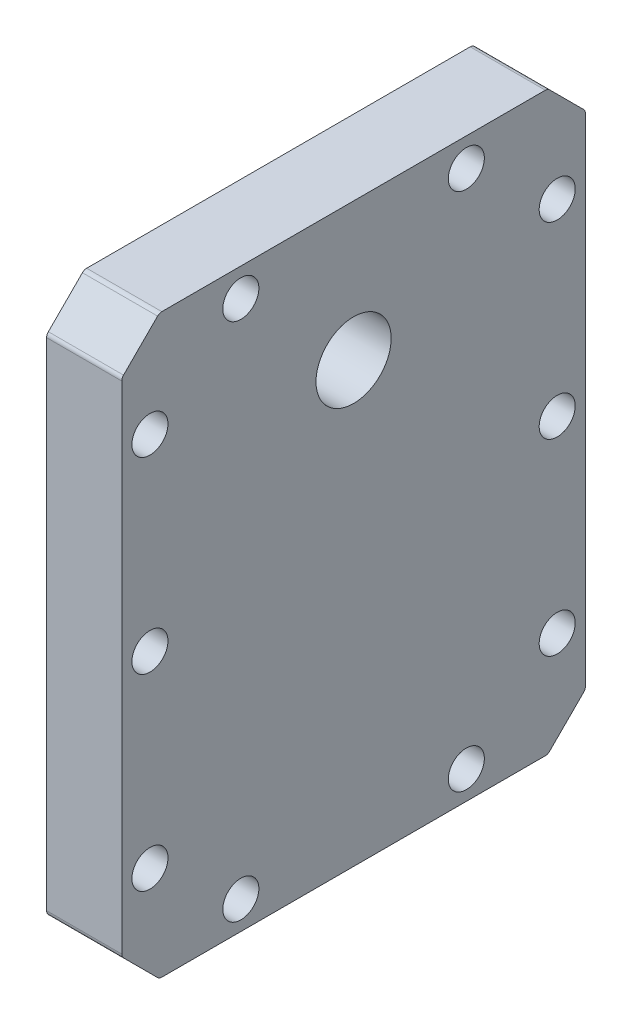
SolidWorks part; units mm, degrees
material "356.0-T6 Permanent Mold cast (SS)"
ref_plane "Front Plane" through (0, 0, 0) normal (1, 0, 0) x (0, 1, 0)
ref_plane "Top Plane" through (0, 0, 0) normal (0, 0, 1) x (0, 1, 0)
ref_plane "Right Plane" through (0, 0, 0) normal (0, 1, 0) x (-1, 0, 0)
sketch "Sketch1" plane through (0, 0, 0) normal (1, 0, 0) x (0, 1, 0)
  line L0 (-8.7312, 0) -> (8.7312, 0) construction
  line L1 (-28.3146, -19.5834) -> (20.3772, -19.5834)
  line L2 (-28.3146, -19.5834) -> (-28.3146, 19.5834)
  line L3 (-28.3146, 19.5834) -> (20.3771, 19.5834)
  line L4 (20.3772, -19.5834) -> (20.3771, 19.5834)
  line L5 (-8.7312, 0) -> (-8.7312, 13.2334) construction
  line L6 (-8.7312, 13.2334) -> (-8.7312, 19.5834) construction
  line L7 (-28.3147, 0) -> (-21.9647, 0) construction
  line L8 (20.3771, 0) -> (14.0271, 0) construction
  circle A0 centre (8.7312, 0) radius 4.7625 construction
  circle A1 centre (-8.7312, 0) radius 12.7 construction
  circle A2 centre (-8.7312, 0) radius 13.2334 construction
  circle A3 centre (8.7312, 0) radius 5.2959 construction
  circle A6 centre (-8.7312, 0) radius 4.7625
  circle A7 centre (8.7312, 0) radius 3.175
  point P0 (0, 0)
  point P9 (0, 0)
  dimension "D1" = 25.4
  dimension "D2" = 9.525
  dimension "D3" = 26.4668
  dimension "D4" = 10.5918
  dimension "D6" = 9.525
  dimension "D7" = 6.35
  dimension "D5" = 6.35
extrude "Boss-Extrude1" add sketch "Sketch1" along normal blind 7.62
chamfer "Chamfer1" distance 3.175 angle 45 4 edges at (3.81, -28.3146, -19.5834) (3.81, 20.3772, -19.5834) (3.81, 20.3771, 19.5834) (3.81, -28.3146, 19.5834)
sketch "Sketch3" plane through (0, 0, 0) normal (-1, 0, 0) x (0, -1, 0)
  line L0 (-20.3771, 0) -> (-15.6146, 0) construction
  line L1 (-20.3772, -16.4084) -> (-20.3771, 16.4084) construction
  line L2 (-17.9959, -9.525) -> (-17.9959, 9.525) construction
  line L3 (3.9687, 19.5834) -> (3.9687, 14.8209) construction
  line L4 (-17.2021, 19.5834) -> (25.1396, 19.5834) construction
  line L5 (-11.9063, 17.2022) -> (19.8437, 17.2022) construction
  line L6 (-11.9062, -17.2021) -> (19.8438, -17.2021) construction
  line L7 (25.9334, -9.525) -> (25.9334, 9.525) construction
  line L16 (-18.2543, -22.1234) -> (26.1918, -22.1234)
  line L17 (26.1918, -22.1234) -> (30.8546, -17.4605)
  line L18 (30.8546, -17.4605) -> (30.8546, 17.4605)
  line L19 (30.8546, 17.4605) -> (26.1918, 22.1234)
  line L20 (26.1918, 22.1234) -> (-18.2543, 22.1234)
  line L21 (-18.2543, 22.1234) -> (-22.9171, 17.4605)
  line L22 (-22.9171, 17.4605) -> (-22.9171, -17.4605)
  line L23 (-22.9171, -17.4605) -> (-18.2543, -22.1234)
  line L24 (-18.2543, -22.1234) -> (26.1918, -22.1234)
  line L25 (26.1918, -22.1234) -> (30.8546, -17.4605)
  line L26 (30.8546, -17.4605) -> (30.8546, 17.4605)
  line L27 (30.8546, 17.4605) -> (26.1918, 22.1234)
  line L28 (26.1918, 22.1234) -> (-18.2543, 22.1234)
  line L29 (-18.2543, 22.1234) -> (-22.9171, 17.4605)
  line L30 (-22.9171, 17.4605) -> (-22.9171, -17.4605)
  line L31 (-22.9171, -17.4605) -> (-18.2543, -22.1234)
  line L63 (23.5521, 14.4357) -> (23.167, 14.8209)
  line L64 (23.5521, -14.4357) -> (23.5521, 14.4357)
  line L65 (23.167, -14.8209) -> (23.5521, -14.4357)
  line L66 (-15.6147, -14.4357) -> (-15.2295, -14.8209)
  line L67 (-15.2295, -14.8209) -> (23.167, -14.8209)
  line L68 (-15.6146, 14.4357) -> (-15.6147, -14.4357)
  line L69 (-15.2295, 14.8209) -> (-15.6146, 14.4357)
  line L70 (23.167, 14.8209) -> (-15.2295, 14.8209)
  line L72 (23.5522, -14.8209) -> (23.5521, 14.8209)
  line L75 (-15.6147, -14.8209) -> (23.5522, -14.8209)
  line L76 (-15.6146, 14.8209) -> (-15.6147, -14.8209)
  line L78 (23.5521, 14.8209) -> (-15.6146, 14.8209)
  circle A0 centre (8.7312, 0) radius 13.2334 construction
  circle A1 centre (-8.7312, 0) radius 5.2959 construction
  point P13 (-17.9959, 0)
  point P26 (3.9687, 17.2021)
  point P30 (3.9687, 17.2022)
  point P31 (-17.9959, 9.525)
  point P32 (-11.9063, 17.2022)
  point P33 (3.9688, -17.2021)
  point P34 (19.8437, 17.2022)
  point P35 (25.9334, 9.525)
  point P36 (25.9334, -9.525)
  point P37 (19.8438, -17.2021)
  point P39 (-11.9062, -17.2021)
  dimension "D3" = 10.5918
  dimension "D4" = 26.4668
  dimension "D5" = 19.05
  dimension "D6" = 31.75
  dimension "D1" = 2.54
  dimension "D2" = 4.7625
extrude "Cut-Extrude2" cut sketch "Sketch3" against normal blind 1.27
hole_wizard "#4 Clearance Hole1" positions "Sketch4" profile "Sketch6" hole size "#4" standard "ANSI Inch" end condition through all
sketch "Sketch4" plane through (1.27, 0, 0) normal (-1, 0, 0) x (0, -1, 0)
  point P0 (-17.9959, 9.525)
  point P3 (-11.9063, 17.2022)
  point P6 (3.9687, 17.2021)
  point P9 (19.8437, 17.2022)
  point P12 (25.9334, 9.525)
  point P15 (25.9334, -9.525)
  point P18 (19.8438, -17.2021)
  point P21 (3.9688, -17.2021)
  point P24 (-11.9062, -17.2021)
  point P27 (-17.9959, -9.525)
sketch "Sketch6" plane through (1.27, 17.9959, 9.525) normal (0, 1, 0) x (0, 0, 1)
  line L0 (0, 0) -> (0, 6.35)
  line L1 (0, 6.35) -> (1.524, 6.35)
  line L2 (1.524, 6.35) -> (1.524, 0)
  line L5 (1.524, 0) -> (0, 0)
  line L11 (0, -6.35) -> (0, 107.95) construction
  dimension "Thru Hole Dia." = 3.048
  dimension "Thru Hole Depth" = 6.35
sketch "Sketch7" plane through (0, 0, 0) normal (-1, 0, 0) x (0, -1, 0)
  circle A0 centre (-8.7312, 0) radius 1.5875
  circle A1 centre (8.7312, 0) radius 3.81
  circle A2 centre (8.7312, 0) radius 6.0325
  circle A3 centre (-8.7312, 0) radius 4.4158
  circle A4 centre (-8.7312, 0) radius 3.175 construction
  circle A5 centre (8.7312, 0) radius 4.7625 construction
  circle M1 centre (-8.7312, 0) radius 3.175
  dimension "D1" = 1.2408
  dimension "D2" = 3.175
  dimension "D3" = 1.27
  dimension "D4" = 7.62
extrude "Boss-Extrude2" add sketch "Sketch7" against normal blind 1.27 contours A3 M1 | A0 M1
sketch "Sketch15" plane through (7.62, 0, 0) normal (1, 0, 0) x (0, 1, 0)
  circle A0 centre (-8.7312, 0) radius 6.0325
  circle A1 centre (-8.7312, 0) radius 4.7625 construction
  dimension "D1" = 1.27
extrude "Boss-Extrude7" add sketch "Sketch15" against normal up to surface (7.62 mm away) up to face at (0, -8.7312, -4.7625)
fillet "Fillet3" radius 6.985 4 edges at (0.635, 15.6147, -14.8209) (0.635, -23.5522, -14.8209) (0.635, -23.5521, 14.8209) (0.635, 15.6146, 14.8209)
fillet "Fillet4" radius 0.508 8 edges at (4.445, -25.1396, -19.5834) (4.445, -28.3146, -16.4084) (4.445, -28.3146, 16.4084) (4.445, -25.1396, 19.5834) (4.445, 17.2021, 19.5834) (4.445, 20.3771, 16.4084) (4.445, 20.3772, -16.4084) (4.445, 17.2021, -19.5834)
